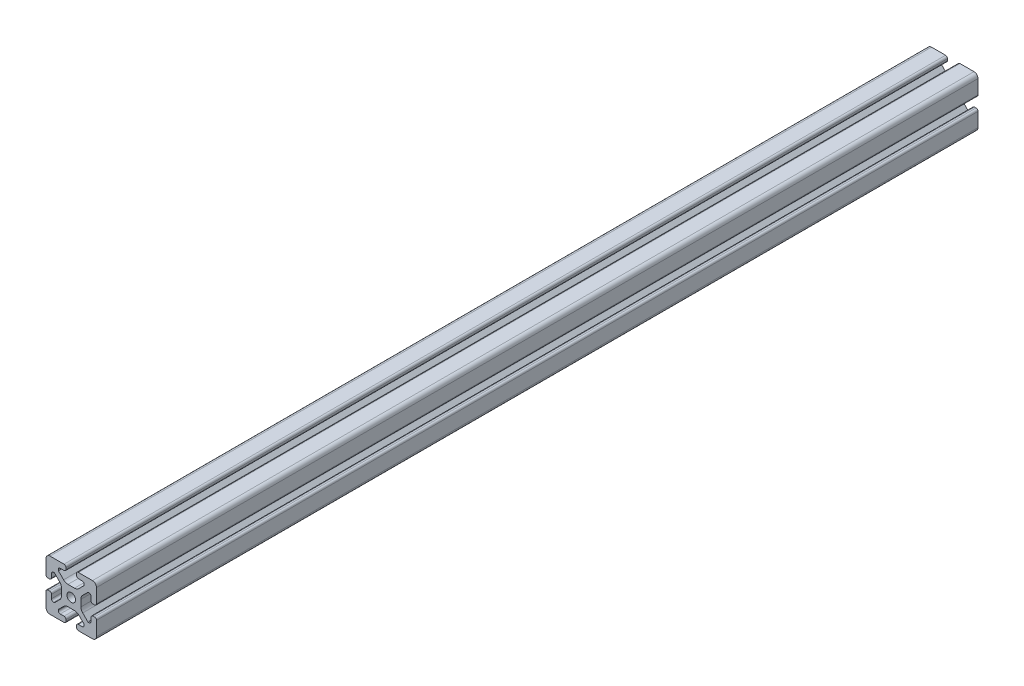
SolidWorks part; units mm, degrees
ref_plane "Front Plane" through (0, 0, 0) normal (0, 0, 1) x (1, 0, 0)
ref_plane "Top Plane" through (0, 0, 0) normal (0, 1, 0) x (1, 0, 0)
ref_plane "Right Plane" through (0, 0, 0) normal (1, 0, 0) x (0, 0, -1)
ref_plane "Plane1" through (0, 0, -4000) normal (0, 0, -1) x (-1, 0, 0)
sketch "Sketch1" plane through (0, 0, -4000) normal (0, 0, -1) x (-1, 0, 0)
  line L0 (16.83, 20) -> (5.6904, 20)
  line L1 (4.1204, 18.43) -> (4.1204, 17.25)
  line L2 (5.6904, 15.68) -> (8.7154, 15.68)
  line L3 (10.2854, 14.11) -> (10.2854, 13.6549)
  line L4 (10.0628, 13.1175) -> (6.0551, 9.1098)
  line L5 (2.6153, 7.685) -> (-2.6153, 7.685)
  line L6 (-6.0551, 9.1098) -> (-10.0628, 13.1175)
  line L7 (-10.2854, 13.6549) -> (-10.2854, 14.11)
  line L8 (-8.7154, 15.68) -> (-5.6904, 15.68)
  line L9 (-4.1204, 17.25) -> (-4.1204, 18.43)
  line L10 (-5.6904, 20) -> (-16.83, 20)
  line L11 (-20, 16.83) -> (-20, 5.6904)
  line L12 (-18.43, 4.1204) -> (-17.25, 4.1204)
  line L13 (-15.68, 5.6904) -> (-15.68, 8.7154)
  line L14 (-14.11, 10.2854) -> (-13.6549, 10.2854)
  line L15 (-13.1175, 10.0628) -> (-9.1098, 6.0551)
  line L16 (-7.685, 2.6153) -> (-7.685, -2.6153)
  line L17 (-9.1098, -6.0551) -> (-13.1175, -10.0628)
  line L18 (-13.6549, -10.2854) -> (-14.11, -10.2854)
  line L19 (-15.68, -8.7154) -> (-15.68, -5.6904)
  line L20 (-17.25, -4.1204) -> (-18.43, -4.1204)
  line L21 (-20, -5.6904) -> (-20, -16.83)
  line L22 (-16.83, -20) -> (-5.6904, -20)
  line L23 (-4.1204, -18.43) -> (-4.1204, -17.25)
  line L24 (-5.6904, -15.68) -> (-8.7154, -15.68)
  line L25 (-10.2854, -14.11) -> (-10.2854, -13.6549)
  line L26 (-10.0628, -13.1175) -> (-6.0551, -9.1098)
  line L27 (-2.6153, -7.685) -> (2.6153, -7.685)
  line L28 (6.0551, -9.1098) -> (10.0628, -13.1175)
  line L29 (10.2854, -13.6549) -> (10.2854, -14.11)
  line L30 (8.7154, -15.68) -> (5.6904, -15.68)
  line L31 (4.1204, -17.25) -> (4.1204, -18.43)
  line L32 (5.6904, -20) -> (16.83, -20)
  line L33 (20, -16.83) -> (20, -5.6904)
  line L34 (18.43, -4.1204) -> (17.25, -4.1204)
  line L35 (15.68, -5.6904) -> (15.68, -8.7154)
  line L36 (14.11, -10.2854) -> (13.6549, -10.2854)
  line L37 (13.1175, -10.0628) -> (9.1098, -6.0551)
  line L38 (7.685, -2.6153) -> (7.685, 2.6153)
  line L39 (9.1098, 6.0551) -> (13.1175, 10.0628)
  line L40 (13.6549, 10.2854) -> (14.11, 10.2854)
  line L41 (15.68, 8.7154) -> (15.68, 5.6904)
  line L42 (17.25, 4.1204) -> (18.43, 4.1204)
  line L43 (20, 5.6904) -> (20, 16.83)
  circle A0 centre (0, 0) radius 3.4
  arc A1 (20, 16.83) -> (16.83, 20) centre (16.83, 16.83) ccw
  arc A2 (5.6904, 20) -> (4.1204, 18.43) centre (5.6904, 18.43) ccw
  arc A3 (4.1204, 17.25) -> (5.6904, 15.68) centre (5.6904, 17.25) ccw
  arc A4 (8.7154, 15.68) -> (10.2854, 14.11) centre (8.7154, 14.11) cw
  arc A5 (10.2854, 13.6549) -> (10.0628, 13.1175) centre (9.5254, 13.6549) cw
  arc A6 (6.0551, 9.1098) -> (2.6153, 7.685) centre (2.6153, 12.5496) cw
  arc A7 (-2.6153, 7.685) -> (-6.0551, 9.1098) centre (-2.6153, 12.5496) cw
  arc A8 (-10.0628, 13.1175) -> (-10.2854, 13.6549) centre (-9.5254, 13.6549) cw
  arc A9 (-10.2854, 14.11) -> (-8.7154, 15.68) centre (-8.7154, 14.11) cw
  arc A10 (-5.6904, 15.68) -> (-4.1204, 17.25) centre (-5.6904, 17.25) ccw
  arc A11 (-4.1204, 18.43) -> (-5.6904, 20) centre (-5.6904, 18.43) ccw
  arc A12 (-16.83, 20) -> (-20, 16.83) centre (-16.83, 16.83) ccw
  arc A13 (-20, 5.6904) -> (-18.43, 4.1204) centre (-18.43, 5.6904) ccw
  arc A14 (-17.25, 4.1204) -> (-15.68, 5.6904) centre (-17.25, 5.6904) ccw
  arc A15 (-15.68, 8.7154) -> (-14.11, 10.2854) centre (-14.11, 8.7154) cw
  arc A16 (-13.6549, 10.2854) -> (-13.1175, 10.0628) centre (-13.6549, 9.5254) cw
  arc A17 (-9.1098, 6.0551) -> (-7.685, 2.6153) centre (-12.5496, 2.6153) cw
  arc A18 (-7.685, -2.6153) -> (-9.1098, -6.0551) centre (-12.5496, -2.6153) cw
  arc A19 (-13.1175, -10.0628) -> (-13.6549, -10.2854) centre (-13.6549, -9.5254) cw
  arc A20 (-14.11, -10.2854) -> (-15.68, -8.7154) centre (-14.11, -8.7154) cw
  arc A21 (-15.68, -5.6904) -> (-17.25, -4.1204) centre (-17.25, -5.6904) ccw
  arc A22 (-18.43, -4.1204) -> (-20, -5.6904) centre (-18.43, -5.6904) ccw
  arc A23 (-20, -16.83) -> (-16.83, -20) centre (-16.83, -16.83) ccw
  arc A24 (-5.6904, -20) -> (-4.1204, -18.43) centre (-5.6904, -18.43) ccw
  arc A25 (-4.1204, -17.25) -> (-5.6904, -15.68) centre (-5.6904, -17.25) ccw
  arc A26 (-8.7154, -15.68) -> (-10.2854, -14.11) centre (-8.7154, -14.11) cw
  arc A27 (-10.2854, -13.6549) -> (-10.0628, -13.1175) centre (-9.5254, -13.6549) cw
  arc A28 (-6.0551, -9.1098) -> (-2.6153, -7.685) centre (-2.6153, -12.5496) cw
  arc A29 (2.6153, -7.685) -> (6.0551, -9.1098) centre (2.6153, -12.5496) cw
  arc A30 (10.0628, -13.1175) -> (10.2854, -13.6549) centre (9.5254, -13.6549) cw
  arc A31 (10.2854, -14.11) -> (8.7154, -15.68) centre (8.7154, -14.11) cw
  arc A32 (5.6904, -15.68) -> (4.1204, -17.25) centre (5.6904, -17.25) ccw
  arc A33 (4.1204, -18.43) -> (5.6904, -20) centre (5.6904, -18.43) ccw
  arc A34 (16.83, -20) -> (20, -16.83) centre (16.83, -16.83) ccw
  arc A35 (20, -5.6904) -> (18.43, -4.1204) centre (18.43, -5.6904) ccw
  arc A36 (17.25, -4.1204) -> (15.68, -5.6904) centre (17.25, -5.6904) ccw
  arc A37 (15.68, -8.7154) -> (14.11, -10.2854) centre (14.11, -8.7154) cw
  arc A38 (13.6549, -10.2854) -> (13.1175, -10.0628) centre (13.6549, -9.5254) cw
  arc A39 (9.1098, -6.0551) -> (7.685, -2.6153) centre (12.5496, -2.6153) cw
  arc A40 (7.685, 2.6153) -> (9.1098, 6.0551) centre (12.5496, 2.6153) cw
  arc A41 (13.1175, 10.0628) -> (13.6549, 10.2854) centre (13.6549, 9.5254) cw
  arc A42 (14.11, 10.2854) -> (15.68, 8.7154) centre (14.11, 8.7154) cw
  arc A43 (15.68, 5.6904) -> (17.25, 4.1204) centre (17.25, 5.6904) ccw
  arc A44 (18.43, 4.1204) -> (20, 5.6904) centre (18.43, 5.6904) ccw
extrude "Boss-Extrude1" add sketch "Sketch1" against normal blind 4000
ref_plane "Plane2" through (0, 0, -698.5) normal (0, 0, -1) x (-1, 0, 0)
sketch "Sketch5" plane through (0, 0, -698.5) normal (0, 0, -1) x (-1, 0, 0)
  line L1 (423.0478, 121.3811) -> (-274.3605, 121.3811)
  line L2 (423.0478, 121.3811) -> (423.0478, -159.1793)
  line L3 (423.0478, -159.1793) -> (-274.3605, -159.1793)
  line L4 (-274.3605, 121.3811) -> (-274.3605, -159.1793)
extrude "Cut-Extrude4" cut sketch "Sketch5" along normal blind 3343.402
